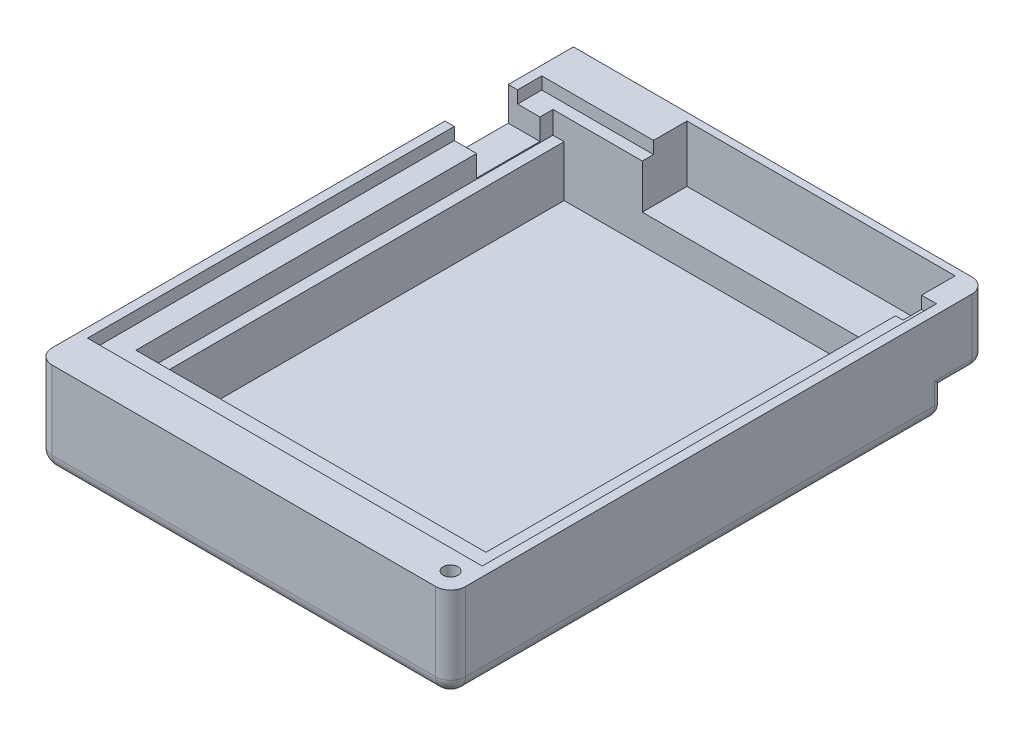
SolidWorks part; units mm, degrees
ref_plane "Front Plane" through (0, 0, 0) normal (0, 0, 1) x (1, 0, 0)
ref_plane "Top Plane" through (0, 0, 0) normal (0, 1, 0) x (1, 0, 0)
ref_plane "Right Plane" through (0, 0, 0) normal (1, 0, 0) x (0, 0, -1)
sketch "Sketch1" plane through (0, 0, 0) normal (0, 1, 0) x (1, 0, 0)
  line L1 (27.75, -36) -> (-27.75, -36)
  line L2 (27.75, -36) -> (27.75, 36)
  line L3 (27.75, 36) -> (-27.75, 36)
  line L4 (-27.75, -36) -> (-27.75, 36)
  line L5 (27.75, -36) -> (-27.75, 36) construction
  line L6 (27.75, 36) -> (-27.75, -36) construction
  point P0 (0, 0)
  dimension "D1" = 55.5
  dimension "D2" = 72
extrude "Boss-Extrude1" add sketch "Sketch1" along normal blind 12.5
sketch "Sketch2" plane through (0, 12.5, 0) normal (0, 1, 0) x (1, 0, 0)
  line L0 (0, 0) -> (0, 25.4065) construction
  line L1 (-26.5, 30.5) -> (26.5, 30.5)
  line L2 (-26.5, 30.5) -> (-26.5, -30.5)
  line L3 (-26.5, -30.5) -> (26.5, -30.5)
  line L4 (26.5, 30.5) -> (26.5, -30.5)
  line L5 (-26.5, 30.5) -> (26.5, -30.5) construction
  line L6 (-26.5, -30.5) -> (26.5, 30.5) construction
  line L8 (27.75, 36) -> (-27.75, 36) construction
  point P0 (0, 0)
  dimension "D1" = 53
  dimension "D2" = 61
  dimension "D3" = 5.5
extrude "Cut-Extrude1" cut sketch "Sketch2" against normal blind 1.65
sketch "Sketch3" plane through (0, 12.5, 0) normal (0, 1, 0) x (1, 0, 0)
  line L0 (0, 0) -> (0, 22.2703) construction
  line L1 (22, 29) -> (-22, 29)
  line L2 (22, 29) -> (22, -34.5)
  line L3 (22, -34.5) -> (-22, -34.5)
  line L4 (-22, 29) -> (-22, -34.5)
  line L5 (22, 29) -> (-22, -34.5) construction
  line L6 (22, -34.5) -> (-22, 29) construction
  line L7 (-27.75, -36) -> (27.75, -36) construction
  point P0 (0, -2.75)
  dimension "D1" = 63.5
  dimension "D2" = 44
  dimension "D3" = 1.5
extrude "Cut-Extrude2" cut sketch "Sketch3" against normal blind 11.5
sketch "Sketch4" plane through (0, 12.5, 0) normal (0, 1, 0) x (1, 0, 0)
  line L1 (22, -34.5) -> (-22, -34.5)
  line L2 (22, -34.5) -> (22, -30.5)
  line L3 (22, -30.5) -> (-22, -30.5)
  line L4 (-22, -34.5) -> (-22, -30.5)
extrude "Boss-Extrude2" add sketch "Sketch4" against normal blind 6.5
sketch "Sketch5" plane through (0, 10.85, 0) normal (0, 1, 0) x (1, 0, 0)
  line L0 (-22, 29) -> (-22, -30.5) construction
  line L1 (22, -30.5) -> (-22, -30.5)
  line L2 (22, -30.5) -> (22, -27)
  line L3 (22, -27) -> (-22, -27)
  line L4 (-22, -30.5) -> (-22, -27)
  dimension "D1" = 3.5
extrude "Boss-Extrude3" add sketch "Sketch5" against normal blind 3
sketch "Sketch6" plane through (0, 10.85, 0) normal (0, 1, 0) x (1, 0, 0)
  line L0 (22, 29) -> (-22, 29) construction
  line L1 (22, -27) -> (23.5, -27)
  line L2 (22, -27) -> (22, 29)
  line L3 (22, 29) -> (23.5, 29)
  line L4 (23.5, -27) -> (23.5, 29)
  line L5 (26.5, -30.5) -> (26.5, 30.5) construction
  line L6 (-26.5, 30.5) -> (-26.5, -30.5) construction
  line L7 (-22, -27) -> (-23.5, -27)
  line L8 (-22, -27) -> (-22, 29)
  line L9 (-22, 29) -> (-23.5, 29)
  line L10 (-23.5, -27) -> (-23.5, 29)
  dimension "D1" = 3
  dimension "D2" = 3
extrude "Cut-Extrude3" cut sketch "Sketch6" against normal blind 3
sketch "Sketch7" plane through (0, 12.5, 0) normal (0, 1, 0) x (1, 0, 0)
  line L0 (-27.75, 36) -> (-27.75, -36) construction
  line L1 (-27.75, 27.25) -> (-20.75, 27.25)
  line L2 (-27.75, 27.25) -> (-27.75, 18.75)
  line L3 (-27.75, 18.75) -> (-20.75, 18.75)
  line L4 (-20.75, 27.25) -> (-20.75, 18.75)
  line L5 (26.5, 30.5) -> (-26.5, 30.5) construction
  dimension "D1" = 8.5
  dimension "D2" = 3.25
  dimension "D3" = 7
extrude "Cut-Extrude4" cut sketch "Sketch7" against normal blind 4.5
sketch "Sketch8" plane through (0, 12.5, 0) normal (0, 1, 0) x (1, 0, 0)
  line L0 (26.5, -30.5) -> (26.5, 30.5) construction
  line L1 (24.5, 28) -> (-11.5, 28)
  line L2 (24.5, 28) -> (24.5, 35)
  line L3 (24.5, 35) -> (-11.5, 35)
  line L4 (-11.5, 28) -> (-11.5, 35)
  line L5 (27.75, 36) -> (-27.75, 36) construction
  line L6 (26.5, 30.5) -> (-26.5, 30.5) construction
  dimension "D1" = 2
  dimension "D2" = 38
  dimension "D3" = 1
  dimension "D4" = 2.5
extrude "Cut-Extrude5" cut sketch "Sketch8" against normal blind 7.6
sketch "Sketch9" plane through (0, 0, -36) normal (0, 0, -1) x (-1, 0, 0)
  line L1 (-27.75, 0) -> (11.5, 0)
  line L2 (-27.75, 0) -> (-27.75, 3.9)
  line L3 (-27.75, 3.9) -> (11.5, 3.9)
  line L4 (11.5, 0) -> (11.5, 3.9)
  line L5 (27.75, 12.5) -> (27.75, 0) construction
  dimension "D1" = 3.9
  dimension "D2" = 16.25
extrude "Cut-Extrude6" cut sketch "Sketch9" against normal blind 6
fillet "Fillet2" radius 2 7 edges at (-19.625, 0, -36) (-27.75, 0, 0) (-27.75, 6.25, 36) (0, 0, 36) (27.75, 6.25, 36) (27.75, 0, 3) (27.75, 8.2, -36)
fillet "Fillet3" radius 1 9 edges at (-11.5, 0, -32) (-11.5, 0.5858, -35.4142) (27.75, 3.9, -32) (27.1642, 3.9, -35.4142) (7.125, 0, -30) (27.1642, 0.5858, -30) (-11.5, 2.95, -36) (7.125, 3.9, -36) (27.75, 2.95, -30)
sketch "Sketch10" plane through (0, 12.5, 0) normal (0, 1, 0) x (1, 0, 0)
  line L0 (27.75, -34) -> (27.75, 34) construction
  line L1 (-25.75, -36) -> (25.75, -36) construction
  circle A0 centre (24.95, -33.2) radius 1
  dimension "D1" = 2
  dimension "D2" = 2.8
  dimension "D3" = 2.8
extrude "Cut-Extrude7" cut sketch "Sketch10" against normal through all
